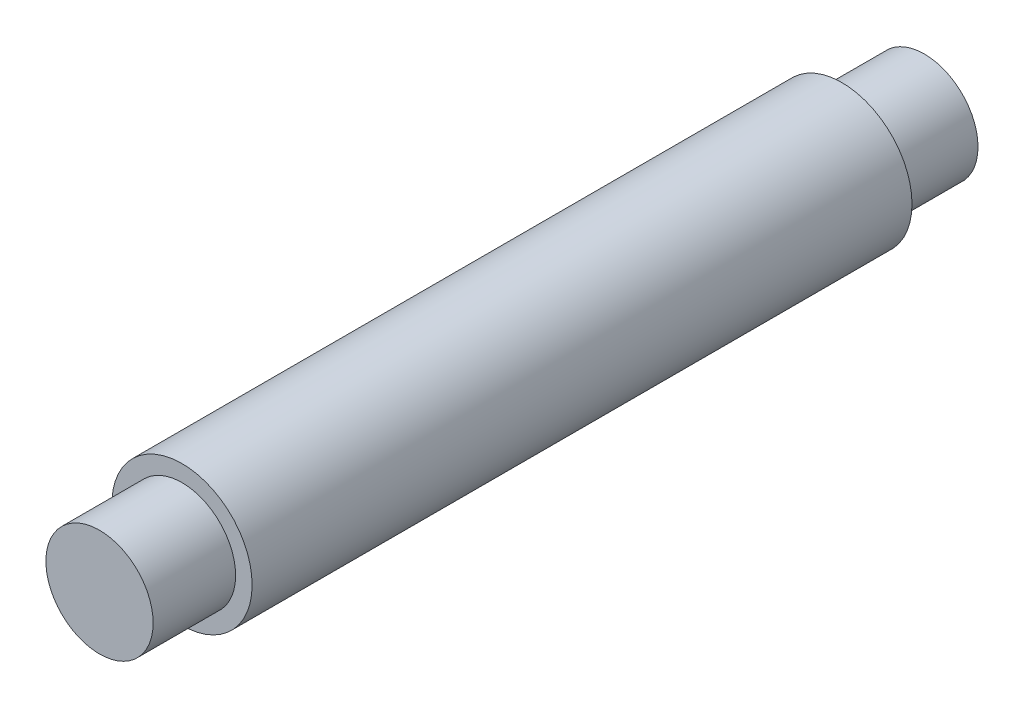
SolidWorks part; units mm, degrees
ref_plane "前视基准面" through (0, 0, 0) normal (0, 0, 1) x (1, 0, 0)
ref_plane "上视基准面" through (0, 0, 0) normal (0, 1, 0) x (1, 0, 0)
ref_plane "右视基准面" through (0, 0, 0) normal (1, 0, 0) x (0, 0, -1)
sketch "草图1" plane through (0, 0, 0) normal (0, 0, 1) x (1, 0, 0)
  circle A0 centre (0, 0) radius 8.5
  dimension "D1" = 17
extrude "凸台-拉伸1" add sketch "草图1" along normal blind 80
sketch "草图2" plane through (0, 0, 80) normal (0, 0, 1) x (1, 0, 0)
  circle A0 centre (0, 0) radius 6.5
  dimension "D1" = 13
extrude "凸台-拉伸2" add sketch "草图2" along normal blind 10
sketch "草图3" plane through (0, 0, 0) normal (0, 0, -1) x (-1, 0, 0)
  circle A0 centre (0, 0) radius 6.5
  dimension "D1" = 13
extrude "凸台-拉伸3" add sketch "草图3" along normal blind 10
